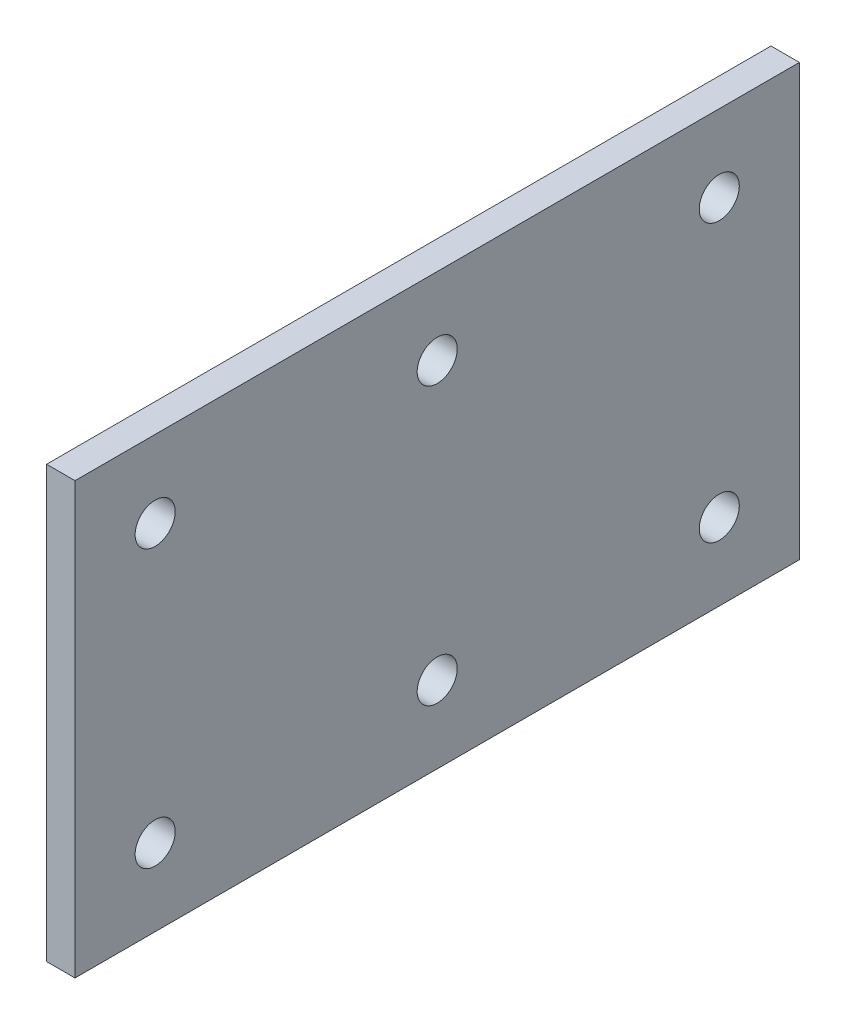
SolidWorks part; units mm, degrees
ref_plane "Front Plane" through (0, 0, 0) normal (0, 0, 1) x (1, 0, 0)
ref_plane "Top Plane" through (0, 0, 0) normal (0, 1, 0) x (1, 0, 0)
ref_plane "Right Plane" through (0, 0, 0) normal (1, 0, 0) x (0, 0, -1)
sketch "Sketch1" plane through (0, 0, 0) normal (1, 0, 0) x (0, 0, -1)
  line L1 (-32.8643, -23.9552) -> (53.2163, -23.9552)
  line L2 (-32.8643, -23.9552) -> (-32.8643, 27.2258)
  line L3 (-32.8643, 27.2258) -> (53.2163, 27.2258)
  line L4 (53.2163, -23.9552) -> (53.2163, 27.2258)
  dimension "D1" = 51.181
  dimension "D2" = 86.0806
extrude "Boss-Extrude1" add sketch "Sketch1" along normal blind 3.3782 contours L2 L3 L4 L1
sketch "Sketch3" plane through (3.3782, 0, 0) normal (1, 0, 0) x (0, 0, -1)
  line L0 (-32.8643, -23.9552) -> (53.2163, -23.9552) construction
  line L1 (53.2163, -23.9552) -> (53.2163, 27.2258) construction
  line L2 (-32.8643, 27.2258) -> (53.2163, 27.2258) construction
  line L3 (-32.8643, -23.9552) -> (-32.8643, 27.2258) construction
  line L4 (10.176, 27.2258) -> (10.176, -23.9552) construction
  circle A0 centre (-23.3393, 18.0818) radius 2.3813
  circle A1 centre (43.6913, 18.0818) radius 2.3812
  circle A2 centre (43.6913, -14.8112) radius 2.3812
  circle A3 centre (-23.3393, -14.8112) radius 2.3813
  circle A4 centre (10.176, 18.0818) radius 2.3813
  circle A5 centre (10.176, -14.8112) radius 2.3813
  dimension "D1" = 4.7625
  dimension "D2" = 4.7625
  dimension "D3" = 4.7625
  dimension "D4" = 4.7625
  dimension "D5" = 9.144
  dimension "D6" = 9.525
  dimension "D13" = 4.7625
  dimension "D14" = 4.7625
  dimension "D15" = 9.144
  dimension "D16" = 9.144
  dimension "D7" = 9.144
  dimension "D8" = 9.144
  dimension "D9" = 9.144
  dimension "D10" = 9.525
  dimension "D11" = 9.525
  dimension "D12" = 9.525
extrude "Cut-Extrude1" cut sketch "Sketch3" against normal up to surface (3.3782 mm away) up to face at (0, 1.6353, -10.176)
